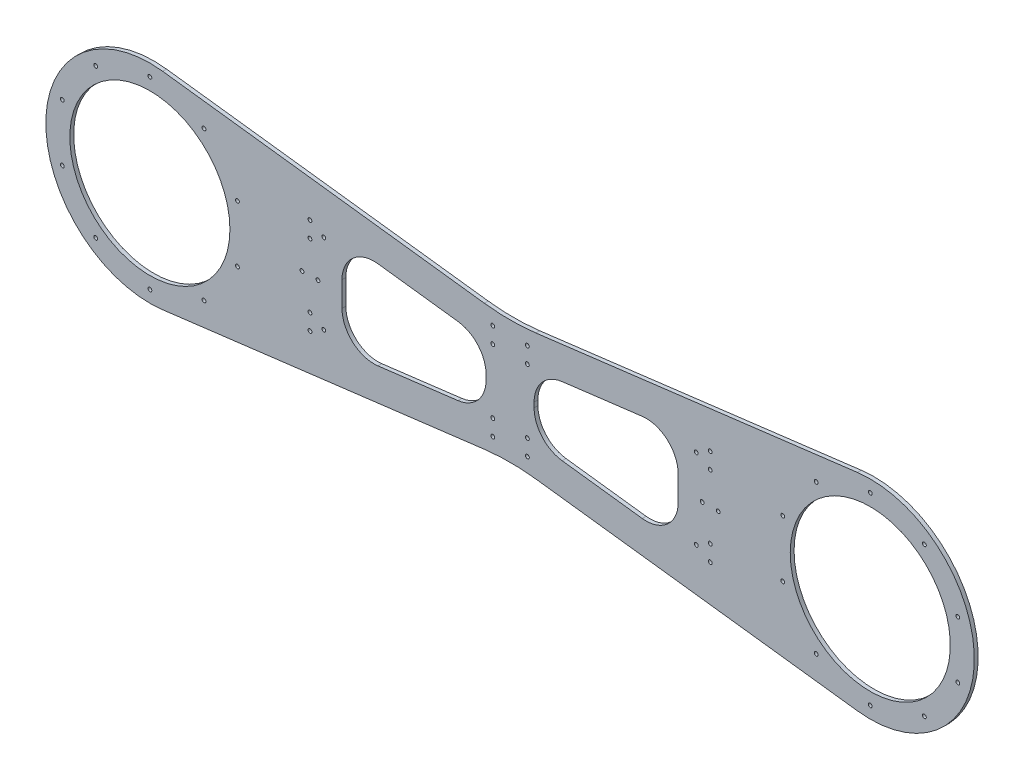
SolidWorks part; units mm, degrees
ref_plane "Front Plane" through (0, 0, 0) normal (0, 0, 1) x (1, 0, 0)
ref_plane "Top Plane" through (0, 0, 0) normal (0, 1, 0) x (1, 0, 0)
ref_plane "Right Plane" through (0, 0, 0) normal (1, 0, 0) x (0, 0, -1)
sketch "Sketch1" plane through (0, 0, 0) normal (0, 0, 1) x (1, 0, 0)
  line L0 (0, 0) -> (0, 959.0652) construction
  line L1 (-75, 96.0624) -> (-75, -96.0624)
  line L2 (-1125, 0) -> (0, 0) construction
  line L3 (-75, -96.0624) -> (-525, -152.0652)
  line L4 (-1084.8631, 322.5121) -> (0, 187.5)
  line L5 (-1084.8631, -322.5121) -> (0, -187.5)
  line L6 (0, -187.5) -> (0, 187.5)
  line L7 (-625, 265.2817) -> (-625, -265.2817) construction
  line L8 (-525, -152.0652) -> (-525, 152.0652)
  line L9 (-525, 152.0652) -> (-75, 96.0624)
  line L10 (-54, 194.2203) -> (-54, -194.2203) construction
  circle A0 centre (-1125, 0) radius 250
  arc A1 (-1084.8631, 322.5121) -> (-1084.8631, -322.5121) centre (-1125, 0) ccw
  circle A2 centre (-1125, 0) radius 287.5 construction
  circle A3 centre (-1125, 287.5) radius 6
  circle A4 centre (-956.0117, 232.5924) radius 6
  circle A5 centre (-851.5713, 88.8424) radius 6
  circle A6 centre (-851.5713, -88.8424) radius 6
  circle A7 centre (-956.0117, -232.5924) radius 6
  circle A8 centre (-1125, -287.5) radius 6
  circle A9 centre (-1293.9883, -232.5924) radius 6
  circle A10 centre (-1398.4287, -88.8424) radius 6
  circle A11 centre (-1398.4287, 88.8424) radius 6
  circle A12 centre (-1293.9883, 232.5924) radius 6
  circle A13 centre (-625, 150) radius 6
  circle A14 centre (-625, 100) radius 6
  circle A15 centre (-581.6987, 125) radius 6
  circle A16 centre (-625, -150) radius 6
  circle A17 centre (-581.6987, -125) radius 6
  circle A18 centre (-625, -100) radius 6
  circle A19 centre (-600, 0) radius 6
  circle A20 centre (-650, 0) radius 6
  circle A21 centre (-54, 150) radius 6
  circle A22 centre (-54, 100) radius 6
  circle A23 centre (-54, -150) radius 6
  circle A24 centre (-54, -100) radius 6
  point P34 (-1125, 0)
  point P56 (-54, 125)
  dimension "D1" = 500
  dimension "D2" = 650
  dimension "D6" = 575
  dimension "D7" = 12
  dimension "D10" = 12
  dimension "D24" = 12
  dimension "D3" = 1125
  dimension "D5" = 375
  dimension "D9" = 625
  dimension "D11" = 50
  dimension "D12" = 50
  dimension "D13" = 50
  dimension "D14" = 150
  dimension "D15" = 25
  dimension "D16" = 25
  dimension "D4" = 100
  dimension "D17" = 100
  dimension "D18" = 75
  dimension "D19" = 100
  dimension "D20" = 54
  dimension "D21" = 125
  dimension "D22" = 25
  dimension "D23" = 25
  dimension "D8" = 10
extrude "Boss-Extrude1" add sketch "Sketch1" along normal blind 12
mirror "Mirror1" about plane through (0, -187.5, 12) normal (-1, 0, 0) of "Boss-Extrude1"
fillet "Fillet1" radius 650 2 edges at (0, -187.5, 6) (0, 187.5, 6)
fillet "Fillet2" radius 100 8 edges at (-75, 96.0624, 6) (-525, 152.0652, 6) (-525, -152.0652, 6) (-75, -96.0624, 6) (525, 152.0652, 6) (525, -152.0652, 6) (75, 96.0624, 6) (75, -96.0624, 6)
equation "\"mbtOD\" = 500"
equation "\"mbtT\" = 6"
equation "\"mbtL\" = 3000"
equation "\"mbtFlangeOD\" = 650"
equation "\"mbtFlangeT\" = 12"
equation "\"mbtFlangeBoltCircleDia\" = 650"
equation "\"mbtFlangeHoleDia\" = 12"
equation "\"mbtOringSize\" = 10 "
equation "\"mbtOringDia\" = 620"
equation "\"D1@Sketch1\"=\"mbtOD\""
equation "\"D2@Sketch1\"=\"mbtFlangeOD\""
equation "\"mbtWidth\" = 2250"
equation "\"D3@Sketch1\"=\"mbtWidth\"/2"
equation "\"D6@Sketch1\"=(\"mbtOD\"+\"mbtFlangeOD\")/2"
equation "\"D7@Sketch1\"=\"mbtFlangeHoleDia\""
equation "\"skiWidth\" = 1250"
equation "\"D9@Sketch1\"=\"skiWidth\"/2"
equation "\"D1@Boss-Extrude1\"=\"mbtFlangeT\""
equation "\"mbtCapL\" = 500"
equation "\"D1@Fillet1\"=\"mbtFlangeOD\""
equation "\"vbtRearOD\" = 800"
equation "\"vbtRearT\" = 6.25"
equation "\"vbtRearFlangeOD\" = 900"
equation "\"vbtRearFlangeT\" = 12"
equation "\"vbtRearBoltHoleDia\" = 12"
equation "\"vbtFrontOD\" = 440"
equation "\"vbtFrontT\" = 25"
equation "\"vbtFrontFlangeOD\" = 510"
equation "\"vbtFrontFlangeT\" = 12"
equation "\"vbtFrontBoltHoleDia\" = 12"
equation "\"D20@Sketch1\"=2*\"vbtRearFlangeT\"+30mm"
